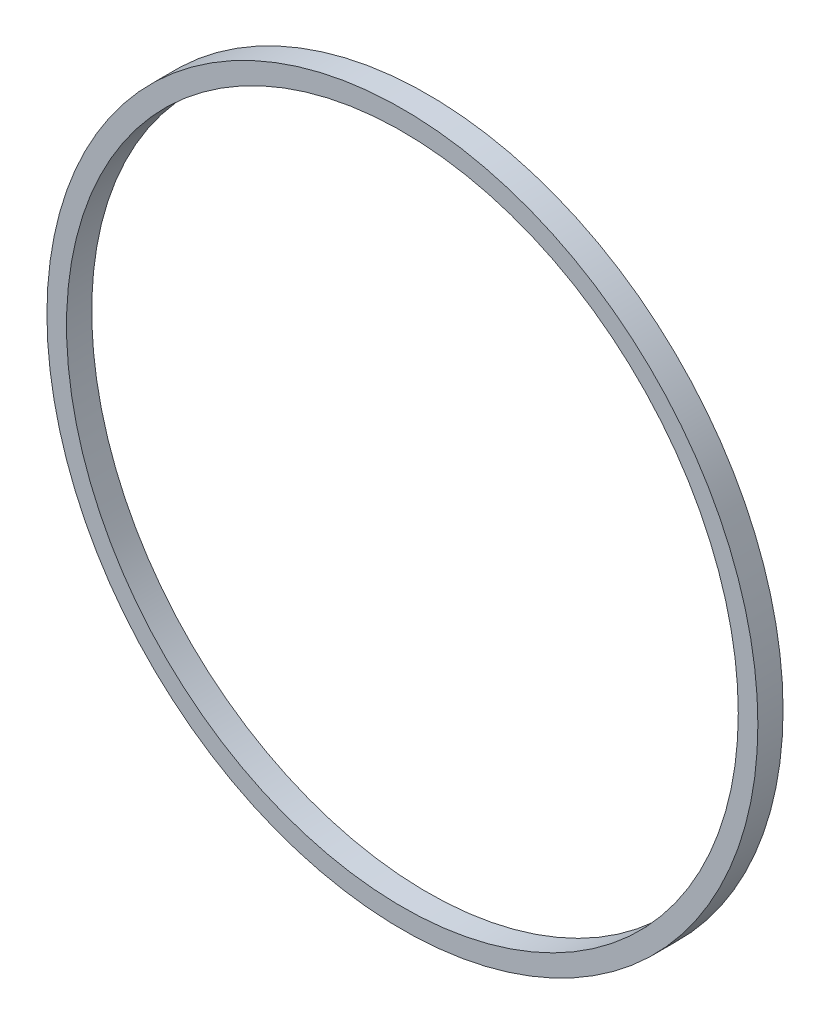
SolidWorks part; units mm, degrees
ref_plane "Front Plane" through (0, 0, 0) normal (0, 0, 1) x (1, 0, 0)
ref_plane "Top Plane" through (0, 0, 0) normal (0, 1, 0) x (1, 0, 0)
ref_plane "Right Plane" through (0, 0, 0) normal (1, 0, 0) x (0, 0, -1)
sketch "Sketch1" plane through (0, 0, 0) normal (0, 0, 1) x (1, 0, 0)
  arc B0 (18.6136, 163.5731) -> (18.6136, 4.963) centre (178.25, 84.268) ccw
  arc B1 (27.2098, 0) -> (164.5701, 79.305) centre (16.0718, 177.9017) ccw
  arc B2 (164.5701, 89.231) -> (27.2098, 168.5361) centre (16.0718, -9.3656) ccw
  circle B3 centre (70.1312, 84.268) radius 63.5
  circle B4 centre (70.1312, 84.268) radius 60
  circle B5 centre (70.1312, 84.268) radius 58.5
  circle B6 centre (70.1312, 84.268) radius 55
sketch_block_instance "sealsblock-1"
sketch_block "sealsblock"
extrude "Boss-Extrude2" add sketch "Sketch1" along normal blind 4.5 contours B3 B4 | B6
